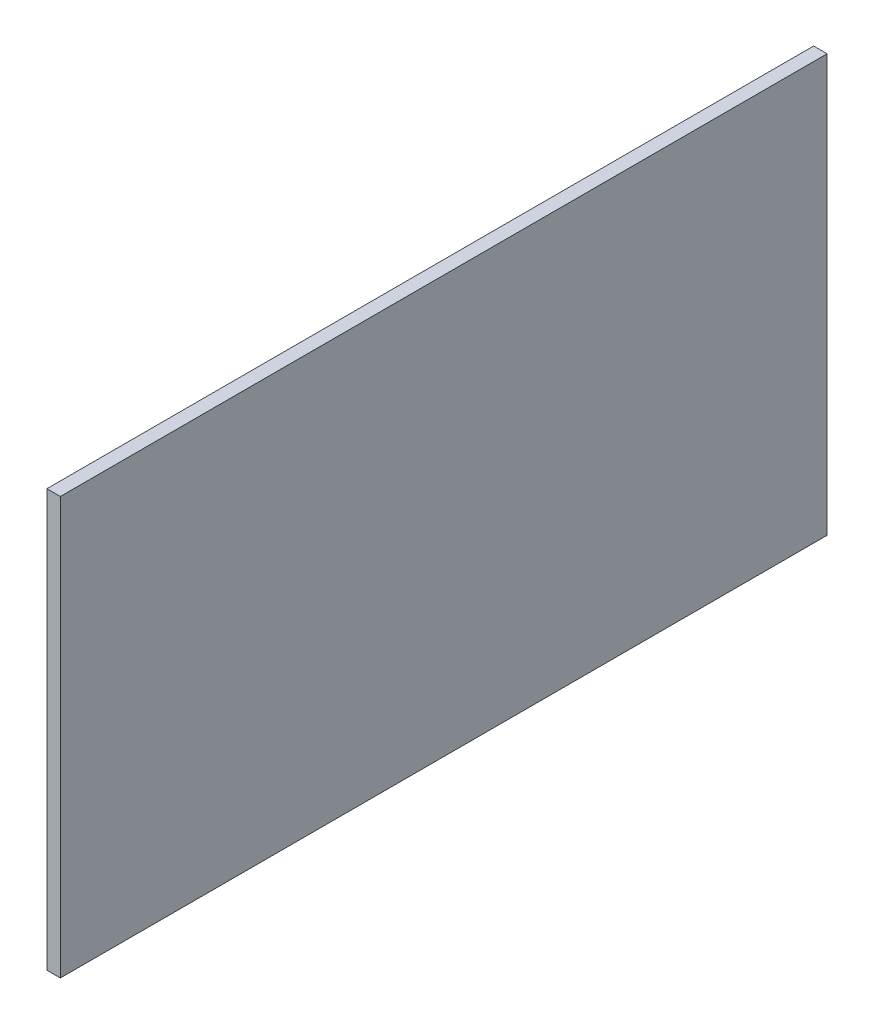
SolidWorks part; units mm, degrees
ref_plane "Front Plane" through (0, 0, 0) normal (0, 0, 1) x (1, 0, 0)
ref_plane "Top Plane" through (0, 0, 0) normal (0, 1, 0) x (1, 0, 0)
ref_plane "Right Plane" through (0, 0, 0) normal (1, 0, 0) x (0, 0, -1)
sketch "Sketch2" plane through (0, 0, 0) normal (1, 0, 0) x (0, 0, -1)
  line L1 (0, 0) -> (1425, 0)
  line L2 (0, 0) -> (0, 775)
  line L3 (0, 775) -> (1425, 775)
  line L4 (1425, 0) -> (1425, 775)
  dimension "D1" = 1425
  dimension "D2" = 775
extrude "Boss-Extrude1" add sketch "Sketch2" along normal blind 25
